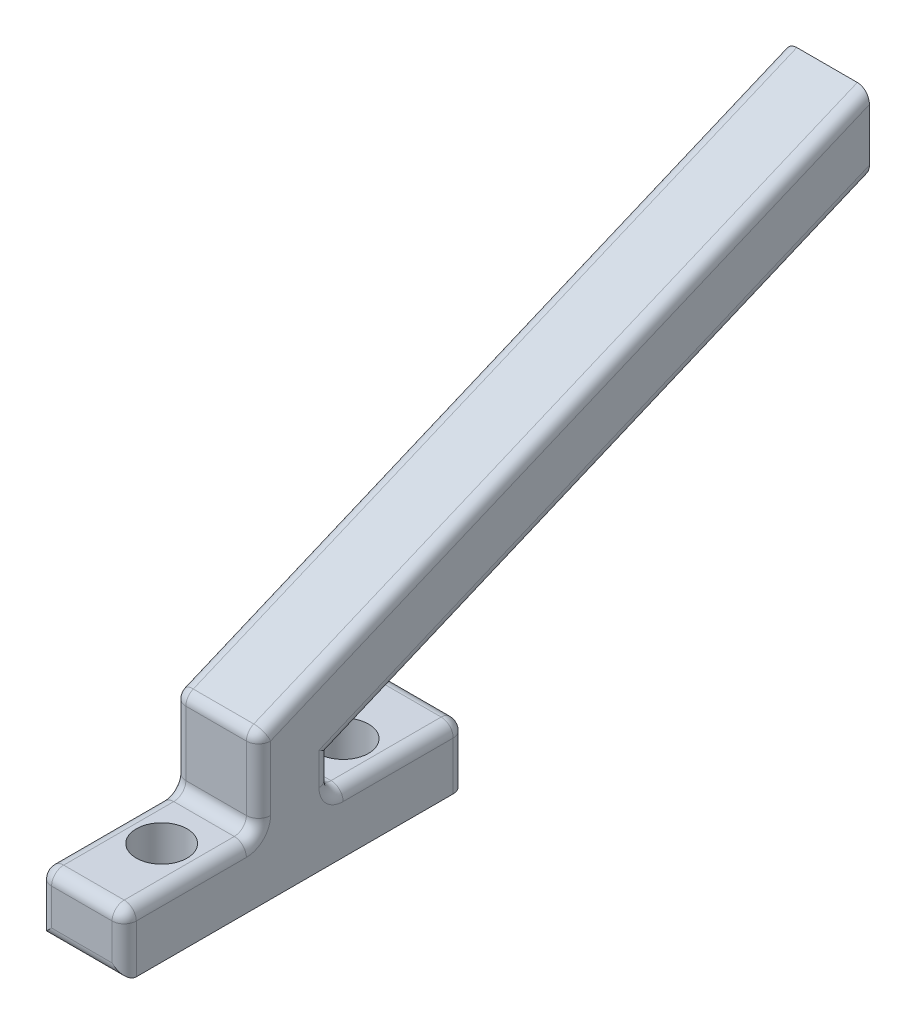
SolidWorks part; units mm, degrees
ref_plane "Front Plane" through (0, 0, 0) normal (1, 0, 0) x (0, 1, 0)
ref_plane "Top Plane" through (0, 0, 0) normal (0, 0, 1) x (0, 1, 0)
ref_plane "Right Plane" through (0, 0, 0) normal (0, 1, 0) x (-1, 0, 0)
sketch "Sketch1" plane through (0, 0, 0) normal (1, 0, 0) x (0, 1, 0)
  line L0 (-5, 21.6) -> (0, 21.6) construction
  line L1 (0, 0) -> (-5, 0)
  line L3 (0, 28.2) -> (-5, 28.2)
  line L4 (-5, 0) -> (-5, 28.2)
  line L9 (-5, 6.6) -> (0, 6.6) construction
  line L10 (-5, 14.1) -> (0, 14.1) construction
  line L11 (0, 14.1) -> (5, 14.1) construction
  line L12 (5, 14.1) -> (24.9723, -33.4) construction
  line L13 (0, 11.1) -> (3.007, 11.1)
  line L14 (3.007, 11.1) -> (21.7179, -33.4)
  line L15 (0, 17.1) -> (6.993, 17.1)
  line L16 (6.993, 17.1) -> (27.7378, -32.2372)
  line L17 (27.7378, -32.2372) -> (28.2267, -33.4)
  line L18 (21.7179, -33.4) -> (28.2267, -33.4)
  line L19 (3.007, 11.1) -> (22.2068, -34.5628) construction
  line L20 (0, 17.1) -> (0, 28.2)
  line L21 (0, 0) -> (0, 11.1)
  dimension "D1" = 15
  dimension "D2" = 5
  dimension "D3" = 6.6
  dimension "D4" = 6.6
  dimension "D5" = 5
  dimension "D6" = 47.5
  dimension "D7" = 3
  dimension "D8" = 3
extrude "Boss-Extrude1" add sketch "Sketch1" along normal blind 7 contours L14 L18 L17 L16 L15 L20 L3 L4 L1 L21 L13
fillet "Fillet1" radius 1 22 edges at (7, 3.4965, 17.1) (0, 3.4965, 17.1) (3.5, 0, 28.2) (7, -2.5, 28.2) (3.5, -5, 28.2) (0, -2.5, 28.2) (7, -2.5, 0) (0, -2.5, 0) (3.5, 0, 17.1) (3.5, 0, 11.1) (3.5, 0, 0) (7, 1.5035, 11.1) (0, 1.5035, 11.1) (0, 0, 5.55) (0, 12.3624, -11.15) (0, 17.6098, -8.15) (7, 17.6098, -8.15) (7, 12.3624, -11.15) (7, 0, 5.55) (0, 0, 22.65) (7, 0, 22.65) (3.5, 6.993, 17.1)
sketch "Sketch2" plane through (0, -5, 0) normal (0, -1, 0) x (1, 0, 0)
  line L0 (3.5, 28.2) -> (3.5, 0) construction
  line L1 (1, 28.2) -> (6, 28.2) construction
  line L2 (6, 0) -> (1, 0) construction
  line L3 (0, 14.1) -> (7, 14.1) construction
  line L4 (0, 1) -> (0, 27.2) construction
  line L5 (7, 1) -> (7, 27.2) construction
  circle A0 centre (3.5, 21.6) radius 2.1
  circle A1 centre (3.5, 6.6) radius 2.1
  dimension "D3" = 4.2
  dimension "D1" = 15
  dimension "D2" = 7.5
extrude "Cut-Extrude1" cut sketch "Sketch2" against normal blind 7
